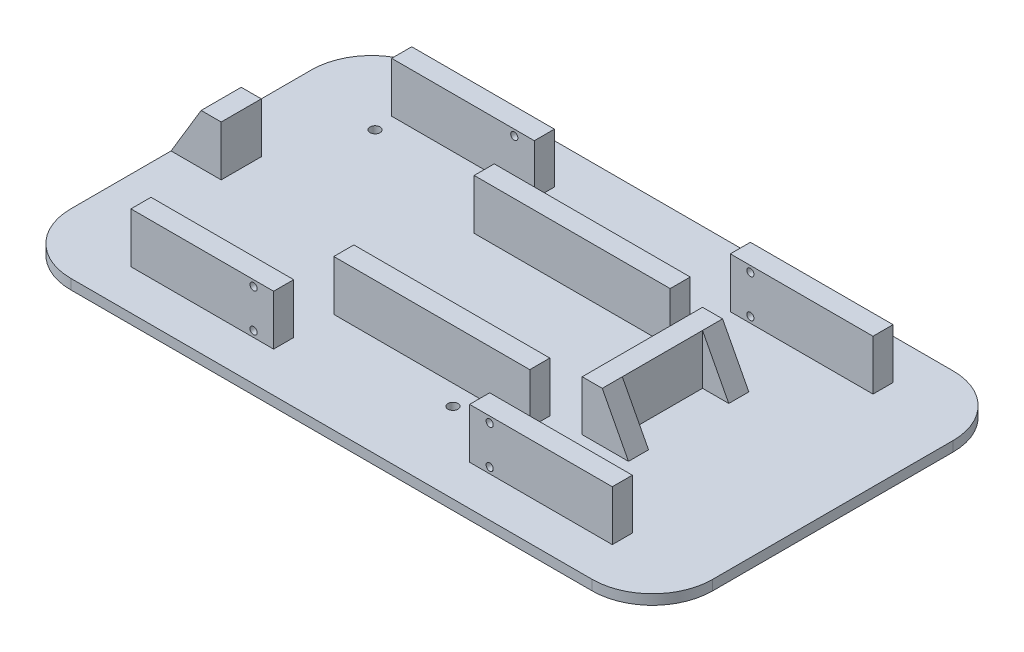
SolidWorks part; units mm, degrees
ref_plane "Front Plane" through (0, 0, 0) normal (0, 0, 1) x (1, 0, 0)
ref_plane "Top Plane" through (0, 0, 0) normal (0, 1, 0) x (1, 0, 0)
ref_plane "Right Plane" through (0, 0, 0) normal (1, 0, 0) x (0, 0, -1)
sketch "Sketch1" plane through (0, 0, 0) normal (0, 1, 0) x (1, 0, 0)
  line L0 (0, 0) -> (0, 74.2227) construction
  line L1 (-130, 90) -> (130, 90)
  line L2 (-160, 60) -> (-160, -60)
  line L3 (-130, -90) -> (130, -90)
  line L4 (160, 60) -> (160, -60)
  line L5 (-160, 90) -> (160, -90) construction
  line L6 (-160, -90) -> (160, 90) construction
  arc A0 (130, -90) -> (160, -60) centre (130, -60) ccw
  arc A1 (-160, -60) -> (-130, -90) centre (-130, -60) ccw
  arc A2 (-130, 90) -> (-160, 60) centre (-130, 60) ccw
  arc A3 (130, 90) -> (160, 60) centre (130, 60) cw
  point P0 (0, 0)
  dimension "D1" = 30
extrude "Boss-Extrude1" add sketch "Sketch1" along normal blind 5
sketch "Sketch2" plane through (0, 5, 0) normal (0, 1, 0) x (1, 0, 0)
  line L0 (0, 0) -> (0, 52.5051) construction
  line L1 (130, 90) -> (-130, 90) construction
  line L2 (-120, 70) -> (-48.8569, 70)
  line L3 (-120, 70) -> (-120, 60)
  line L4 (-120, 60) -> (-48.8569, 60)
  line L5 (-48.8569, 70) -> (-48.8569, 60)
  line L6 (-120, 70) -> (-48.8569, 60) construction
  line L7 (-120, 60) -> (-48.8569, 70) construction
  line L8 (-160, 60) -> (-160, -60) construction
  line L9 (120, 60) -> (48.8569, 60)
  line L10 (48.8569, 70) -> (48.8569, 60)
  line L11 (120, 70) -> (48.8569, 70)
  line L12 (120, 70) -> (120, 60)
  line L13 (0, 0) -> (56.1733, 0) construction
  line L14 (120, -70) -> (120, -60)
  line L15 (120, -70) -> (48.8569, -70)
  line L16 (48.8569, -70) -> (48.8569, -60)
  line L17 (120, -60) -> (48.8569, -60)
  line L18 (-120, -60) -> (-48.8569, -60)
  line L19 (-48.8569, -70) -> (-48.8569, -60)
  line L20 (-120, -70) -> (-48.8569, -70)
  line L21 (-120, -70) -> (-120, -60)
  point P3 (-84.4284, 65)
  dimension "D1" = 20
  dimension "D2" = 40
extrude "Boss-Extrude3" add sketch "Sketch2" along normal blind 25
sketch "Sketch3" plane through (0, 5, 0) normal (0, 1, 0) x (1, 0, 0)
  line L0 (-160, 60) -> (-160, -60) construction
  line L5 (0, 0) -> (-153.5701, 0) construction
  line L10 (-145, 0) -> (-135, 0)
  line L11 (-145, 0) -> (-145, -10)
  line L12 (-145, -10) -> (-135, -10)
  line L13 (-135, 0) -> (-135, -10)
  dimension "D1" = 10
  dimension "D2" = 10
  dimension "D3" = 15
extrude "Boss-Extrude4" add sketch "Sketch3" along normal blind 25
sketch "Sketch5" plane through (0, 0, 0) normal (0, 0, -1) x (-1, 0, 0)
  line L0 (145, 5) -> (145, 30)
  line L1 (160, 5) -> (130, 5) construction
  line L2 (145, 30) -> (160, 5)
  line L3 (160, 5) -> (145, 5)
extrude "Boss-Extrude5" add sketch "Sketch5" against normal up to surface (10 mm away) up to face at (-140, 17.5, 10)
sketch "Sketch6" plane through (0, 5, 0) normal (0, 1, 0) x (1, 0, 0)
  line L5 (0, 0) -> (65, 0) construction
  line L6 (-135, -10) -> (-135, 0) construction
  line L8 (65, -30) -> (65, 30)
  line L9 (65, 30) -> (75, 30)
  line L10 (75, -30) -> (75, 30)
  line L11 (65, -30) -> (75, -30)
  line L12 (75, 0) -> (136.007, 0) construction
  line L13 (120, -60) -> (48.8569, -60) construction
  line L14 (48.8569, 60) -> (120, 60) construction
  dimension "D1" = 200
  dimension "D2" = 10
  dimension "D3" = 60
extrude "Boss-Extrude6" add sketch "Sketch6" along normal blind 25
sketch "Sketch8" plane through (0, 0, 30) normal (0, 0, 1) x (1, 0, 0)
  line L0 (75, 30) -> (88.0852, 5)
  line L1 (130, 5) -> (-130, 5) construction
  line L2 (88.0852, 5) -> (75, 5)
  line L3 (75, 5) -> (75, 30)
extrude "Boss-Extrude7" add sketch "Sketch8" against normal blind 10
ref_plane "Plane1" through (0, 0, 0) normal (0, 0, -1) x (-1, 0, 0)
mirror "Mirror1" about plane through (0, 0, 0) normal (0, 0, -1) of "Boss-Extrude7"
mirror "Mirror2" about plane through (-145, 30, 0) normal (0, 0, 1) of "Boss-Extrude4", "Boss-Extrude5"
sketch "Sketch9" plane through (0, 5, 0) normal (0, 1, 0) x (1, 0, 0)
  line L1 (48.8569, -30) -> (-48.8569, -30)
  line L2 (48.8569, -30) -> (48.8569, -40)
  line L3 (48.8569, -40) -> (-48.8569, -40)
  line L4 (-48.8569, -30) -> (-48.8569, -40)
  line L5 (48.8569, -60) -> (48.8569, -70) construction
  line L6 (-48.8569, -70) -> (-48.8569, -60) construction
  line L7 (65, -30) -> (88.0852, -30) construction
  dimension "D1" = 0
  dimension "D2" = 0
  dimension "D3" = 0
  dimension "D4" = 10
extrude "Boss-Extrude8" add sketch "Sketch9" along normal blind 25
mirror "Mirror3" about plane through (0, 0, 0) normal (0, 0, -1) of "Boss-Extrude8"
sketch "Sketch11" plane through (0, 5, 0) normal (0, 1, 0) x (1, 0, 0)
  line L0 (-120, 60) -> (-48.8569, 60) construction
  line L2 (7.1969, 0) -> (-7.1969, 0) construction
  line L3 (-48.8569, 30) -> (-48.8569, 40) construction
  circle A0 centre (-118.2757, 50) radius 2.5
  circle A1 centre (-118.2757, -50) radius 2.5
  circle A2 centre (20.5619, -50) radius 2.5
  circle A3 centre (20.5619, 50) radius 2.5
  dimension "D1" = 5
  dimension "D2" = 10
extrude "Cut-Extrude1" cut sketch "Sketch11" against normal up to surface (5 mm away) up to face at (0, 0, 0)
sketch "Sketch12" plane through (0, 0, 70) normal (0, 0, 1) x (1, 0, 0)
  line L0 (-120, 30) -> (-48.8569, 30) construction
  line L1 (-48.8569, 30) -> (-48.8569, 5) construction
  line L2 (-48.8569, 17.5) -> (-58.3196, 17.5) construction
  line L3 (-48.8569, 30) -> (-48.8569, 5) construction
  line L4 (0, -16.5) -> (0, 16.5) construction
  circle A0 centre (-58.8569, 27) radius 1.7889
  circle A1 centre (-58.8569, 8) radius 1.7889
  circle A2 centre (58.8569, 8) radius 1.7889
  circle A3 centre (58.8569, 27) radius 1.7889
  dimension "D1" = 3
  dimension "D2" = 10
extrude "Cut-Extrude2" cut sketch "Sketch12" against normal blind 10
mirror "Mirror4" about plane through (0, 0, 0) normal (0, 0, 1) of "Cut-Extrude2"
